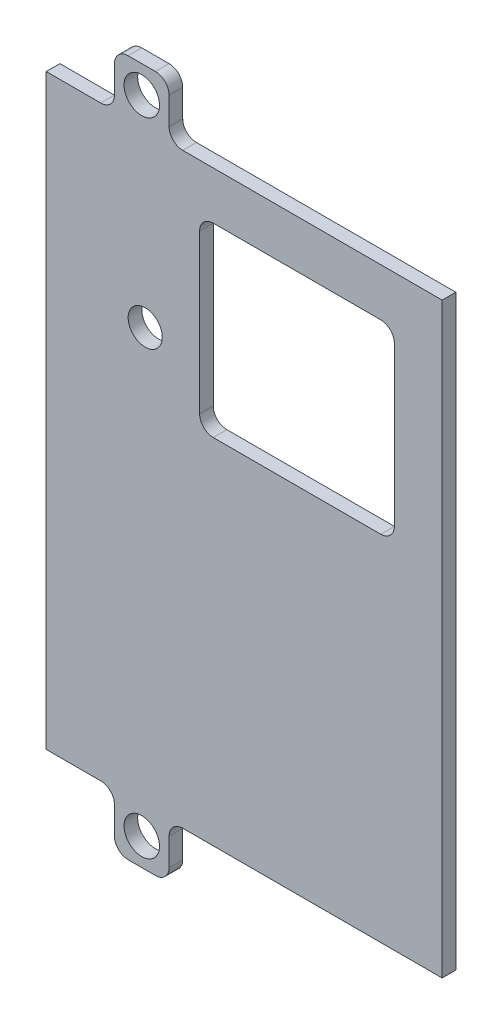
SolidWorks part; units mm, degrees
ref_plane "Front Plane" through (0, 0, 0) normal (0, 0, 1) x (1, 0, 0)
ref_plane "Top Plane" through (0, 0, 0) normal (0, 1, 0) x (1, 0, 0)
ref_plane "Right Plane" through (0, 0, 0) normal (1, 0, 0) x (0, 0, -1)
sketch "Sketch1" plane through (0, 0, 0) normal (0, 0, 1) x (1, 0, 0)
  line L35 (19.05, 113.03) -> (19.05, 107.95)
  line L36 (11.43, 115.57) -> (16.51, 115.57)
  line L37 (8.89, 107.95) -> (8.89, 113.03)
  line L38 (19.05, 113.03) -> (19.05, 107.95)
  line L39 (11.43, 115.57) -> (16.51, 115.57)
  line L40 (8.89, 107.95) -> (8.89, 113.03)
  line L50 (6.35, -3.81) -> (-3.81, -3.81)
  line L51 (-3.81, -3.81) -> (-3.81, 105.41)
  line L52 (-3.81, 105.41) -> (6.35, 105.41)
  line L53 (19.05, -6.35) -> (19.05, -11.43)
  line L54 (16.51, -13.97) -> (11.43, -13.97)
  line L55 (8.89, -11.43) -> (8.89, -6.35)
  line L56 (19.05, -6.35) -> (19.05, -11.43)
  line L57 (16.51, -13.97) -> (11.43, -13.97)
  line L58 (8.89, -11.43) -> (8.89, -6.35)
  line L59 (21.59, 105.41) -> (69.85, 105.41)
  line L60 (69.85, 105.41) -> (69.85, -3.81)
  line L61 (69.85, -3.81) -> (21.59, -3.81)
  line L66 (60.96, 96.52) -> (60.96, 61.9754)
  line L67 (24.7281, 101.346) -> (24.7281, 59.5821) construction
  line L68 (24.7281, 96.52) -> (24.7281, 61.9754)
  line L69 (24.7281, 61.9754) -> (60.96, 61.9754)
  line L71 (24.7281, 96.52) -> (60.96, 96.52)
  circle A31 centre (13.97, 110.49) radius 3.302
  circle A32 centre (13.97, 110.49) radius 3.302
  circle A34 centre (13.97, -8.89) radius 3.302
  circle A35 centre (13.97, -8.89) radius 3.302
  arc A56 (19.05, 107.95) -> (21.59, 105.41) centre (21.59, 107.95) ccw
  arc A57 (19.05, 113.03) -> (16.51, 115.57) centre (16.51, 113.03) ccw
  arc A58 (11.43, 115.57) -> (8.89, 113.03) centre (11.43, 113.03) ccw
  arc A59 (6.35, 105.41) -> (8.89, 107.95) centre (6.35, 107.95) ccw
  arc A60 (19.05, 107.95) -> (21.59, 105.41) centre (21.59, 107.95) ccw
  arc A61 (19.05, 113.03) -> (16.51, 115.57) centre (16.51, 113.03) ccw
  arc A62 (11.43, 115.57) -> (8.89, 113.03) centre (11.43, 113.03) ccw
  arc A63 (6.35, 105.41) -> (8.89, 107.95) centre (6.35, 107.95) ccw
  circle A76 centre (14.6071, 73.3808) radius 3.175
  arc A80 (21.59, -3.81) -> (19.05, -6.35) centre (21.59, -6.35) ccw
  arc A81 (16.51, -13.97) -> (19.05, -11.43) centre (16.51, -11.43) ccw
  arc A82 (8.89, -11.43) -> (11.43, -13.97) centre (11.43, -11.43) ccw
  arc A83 (8.89, -6.35) -> (6.35, -3.81) centre (6.35, -6.35) ccw
  arc A84 (21.59, -3.81) -> (19.05, -6.35) centre (21.59, -6.35) ccw
  arc A85 (16.51, -13.97) -> (19.05, -11.43) centre (16.51, -11.43) ccw
  arc A86 (8.89, -11.43) -> (11.43, -13.97) centre (11.43, -11.43) ccw
  arc A87 (8.89, -6.35) -> (6.35, -3.81) centre (6.35, -6.35) ccw
  point P11 (33.02, 96.52)
  dimension "D9" = 6.35
  dimension "D7" = 8.89
  dimension "D1" = 0
  dimension "D2" = 0
  dimension "D3" = 0
  dimension "D4" = 0
extrude "Boss-Extrude1" add sketch "Sketch1" along normal blind 2.54
sketch "Sketch3" plane through (0, 0, 0) normal (0, 0, -1) x (-1, 0, 0)
  line L0 (-69.85, -3.81) -> (-21.59, -3.81) construction
  line L1 (-37.846, -3.81) -> (-46.99, -3.81)
  line L2 (-37.846, -3.81) -> (-37.846, 0)
  line L3 (-37.846, 0) -> (-46.99, 0)
  line L4 (-46.99, -3.81) -> (-46.99, 0)
  line L5 (-37.846, -3.81) -> (-37.846, 0) construction
extrude "Boss-Extrude2" add sketch "Sketch3" along normal blind 8.89
fillet "Fillet1" radius 2.54 4 edges at (60.96, 61.9754, 1.27) (60.96, 96.52, 1.27) (24.7281, 96.52, 1.27) (24.7281, 61.9754, 1.27)
